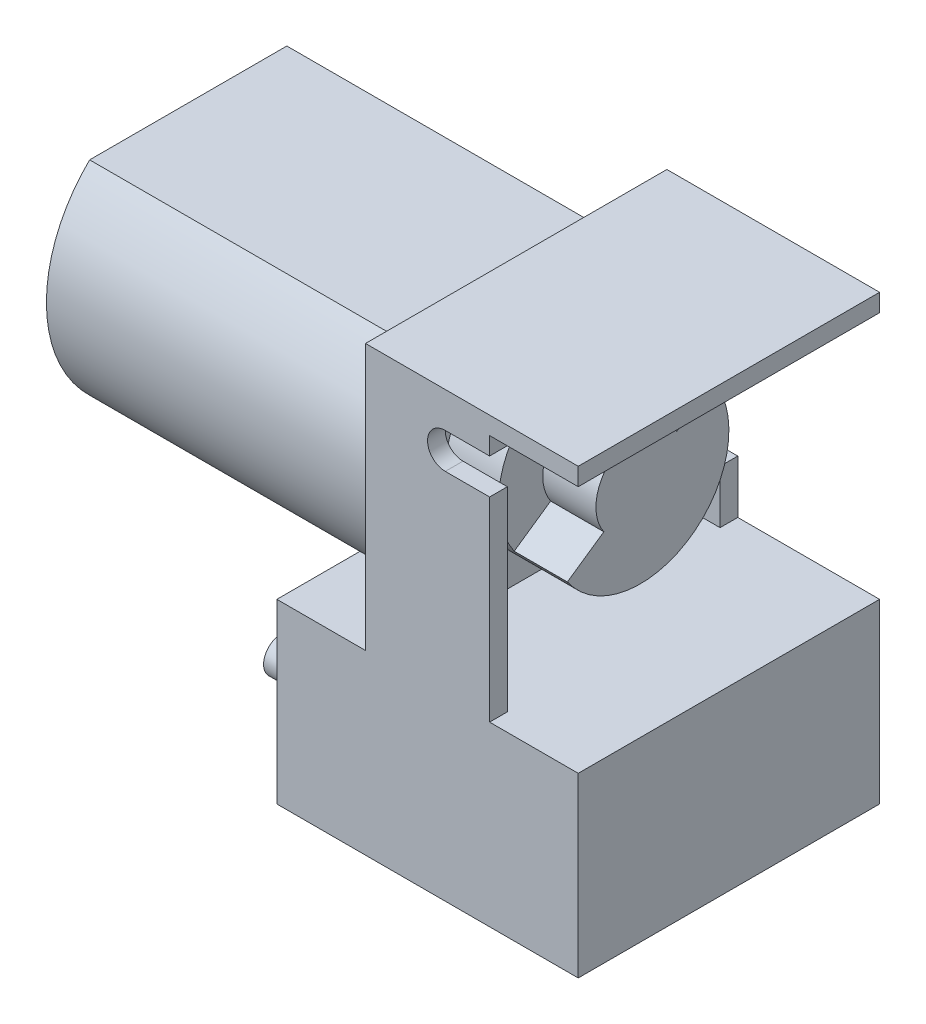
SolidWorks part; units mm, degrees
ref_plane "Front Plane" through (0, 0, 0) normal (0, 0, 1) x (1, 0, 0)
ref_plane "Top Plane" through (0, 0, 0) normal (0, 1, 0) x (1, 0, 0)
ref_plane "Right Plane" through (0, 0, 0) normal (1, 0, 0) x (0, 0, -1)
sketch "Sketch1" plane through (0, 0, 0) normal (0, 0, 1) x (1, 0, 0)
  line L0 (-8.5, 5) -> (-8.5, -5)
  line L1 (-8.5, 5) -> (8.5, 5) construction
  line L2 (-8.5, 5) -> (-8.5, -5) construction
  line L3 (-8.5, -5) -> (8.5, -5) construction
  line L4 (8.5, 5) -> (8.5, -5) construction
  line L5 (-8.5, 5) -> (8.5, -5) construction
  line L6 (-8.5, -5) -> (8.5, 5) construction
  line L7 (-8.5, -5) -> (8.5, -5)
  line L8 (8.5, -5) -> (8.5, 5)
  line L9 (8.5, 5) -> (3.5, 5)
  line L10 (3.5, 5) -> (3.5, 16)
  line L11 (3.5, 16) -> (1, 16)
  line L12 (1, 18) -> (3.5, 18)
  line L13 (3.5, 18) -> (3.5, 19)
  line L14 (3.5, 19) -> (8.5, 19)
  line L15 (8.5, 19) -> (8.5, 20)
  line L16 (8.5, 20) -> (-3.5, 20)
  line L17 (-3.5, 20) -> (-3.5, 5)
  line L18 (-3.5, 5) -> (-8.5, 5)
  arc A0 (1, 16) -> (1, 18) centre (1, 17) cw
  point P0 (0, 0)
  point P11 (0, 0)
  point P18 (0, 0)
  dimension "D1" = 17
  dimension "D2" = 10
  dimension "D3" = 15
  dimension "D4" = 7
  dimension "D5" = 5
  dimension "D6" = 2.5
  dimension "D7" = 2
  dimension "D8" = 1
  dimension "D9" = 1
extrude "Boss-Extrude1" add sketch "Sketch1" along normal mid plane 17
sketch "Sketch2" plane through (0, 0, 0) normal (1, 0, 0) x (0, 0, -1)
  line L0 (-8.5, 19) -> (8.5, 19) construction
  line L1 (-7.5, 19) -> (8.5, 19)
  line L2 (-7.5, 19) -> (-7.5, 5)
  line L3 (-7.5, 5) -> (8.5, 5)
  line L4 (8.5, 19) -> (8.5, 5)
  line L5 (-8.5, 20) -> (-8.5, 5) construction
  dimension "D1" = 1
extrude "Cut-Extrude1" cut sketch "Sketch2" against normal offset from surface 1 and the other way through all up to face at (-3.5, 12.5, 0)
sketch "Sketch3" plane through (0, 0, -8.5) normal (0, 0, -1) x (-1, 0, 0)
  line L0 (-0.5, 8) -> (2.5, 5) construction
  line L1 (2.5, 5) -> (-0.5, 5)
  line L2 (2.5, 5) -> (2.5, 8)
  line L3 (2.5, 8) -> (-0.5, 8)
  line L4 (-0.5, 5) -> (-0.5, 8)
  circle A0 centre (1, 6.5) radius 0.6
  point P7 (0, 0)
  point P8 (1.5871, 6.9072)
  point P9 (1, 6.5)
  dimension "D3" = 1.2
  dimension "D1" = 3
  dimension "D2" = 3
extrude "Boss-Extrude2" add sketch "Sketch3" against normal blind 1
sketch "Sketch4" plane through (-3.5, 0, 0) normal (-1, 0, 0) x (0, 0, 1)
  line L0 (-8.5, 20) -> (8.5, 5) construction
  line L1 (-5.5621, 18.25) -> (5.5621, 18.25)
  line L2 (5.5621, 6.75) -> (-5.5621, 6.75)
  line L3 (-5.5621, 6.75) -> (5.5621, 18.25) construction
  arc A0 (-5.5621, 18.25) -> (-5.5621, 6.75) centre (0, 12.5) ccw
  arc A1 (5.5621, 6.75) -> (5.5621, 18.25) centre (0, 12.5) ccw
  point P10 (0, 12.5)
  point P11 (7.1558, 16.0768)
  dimension "D1" = 8
  dimension "D2" = 11.5
extrude "Boss-Extrude3" add sketch "Sketch4" along normal blind 18.5
sketch "Sketch5" plane through (-2.5, 0, 0) normal (1, 0, 0) x (0, 0, -1)
  line L0 (-8.5, 20) -> (8.5, 5) construction
  circle A0 centre (0, 12.5) radius 5
  dimension "D1" = 10
extrude "Boss-Extrude4" add sketch "Sketch5" along normal blind 6
sketch "Sketch6" plane through (3.5, 0, 0) normal (1, 0, 0) x (0, 0, -1)
  line L0 (4.1115, 15.3452) -> (2.0558, 13.9226)
  line L1 (-2.0558, 11.0774) -> (-4.1115, 9.6548)
  line L2 (2.0558, 13.9226) -> (-2.0558, 11.0774) construction
  arc A0 (2.0558, 13.9226) -> (-2.0558, 11.0774) centre (0, 12.5) ccw
  circle A1 centre (0, 12.5) radius 5
  arc A2 (4.1115, 15.3452) -> (-4.1115, 9.6548) centre (0, 12.5) ccw
  circle A3 centre (0, 12.5) radius 5 construction
  point P0 (2.0558, 13.9226)
  dimension "D2" = 5
  dimension "D1" = 0
extrude "Cut-Extrude2" cut sketch "Sketch6" against normal blind 3
sketch "Sketch7" plane through (-8.5, 0, 0) normal (-1, 0, 0) x (0, 0, 1)
  line L0 (-3.75, -2.3018) -> (3.75, -2.3018) construction
  circle A0 centre (-3.75, -2.3018) radius 1
  circle A1 centre (3.75, -2.3018) radius 1
  circle A2 centre (-3.75, -2.3018) radius 0.7
  circle A3 centre (3.75, -2.3018) radius 0.7
  point P4 (0, -2.3018)
  dimension "D2" = 2
  dimension "D3" = 1.4
  dimension "D1" = 7.5
extrude "Boss-Extrude5" add sketch "Sketch7" along normal blind 4.5
